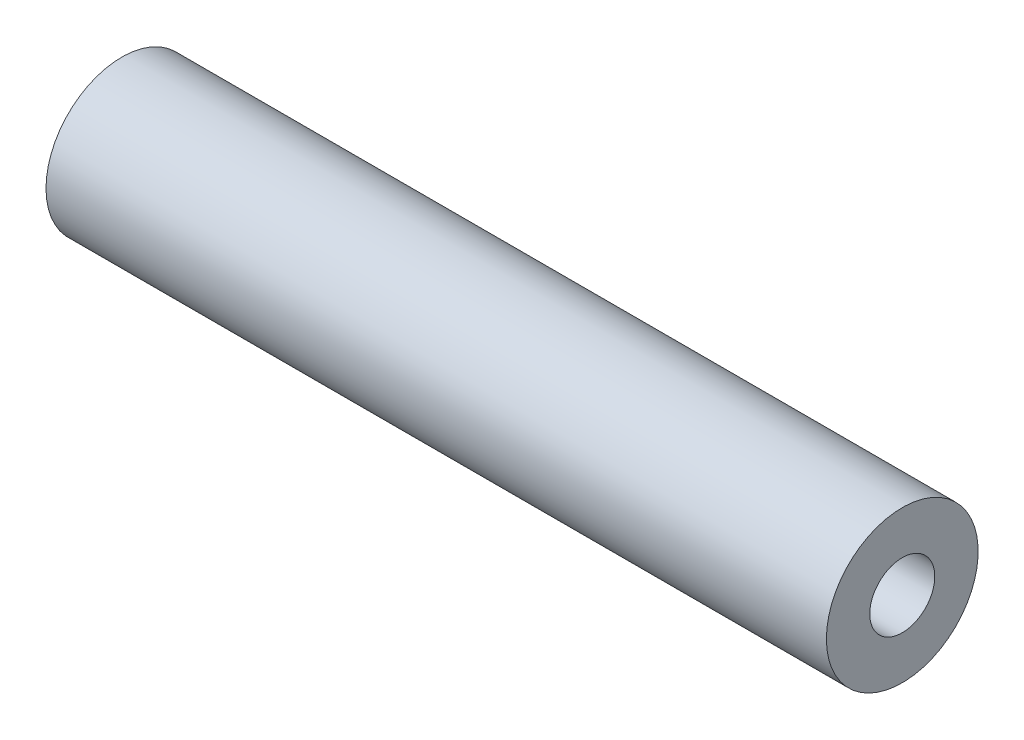
SolidWorks part; units mm, degrees
ref_plane "Front Plane" through (0, 0, 0) normal (0, 0, 1) x (1, 0, 0)
ref_plane "Top Plane" through (0, 0, 0) normal (0, 1, 0) x (1, 0, 0)
ref_plane "Right Plane" through (0, 0, 0) normal (1, 0, 0) x (0, 0, -1)
sketch "Sketch1" plane through (0, 0, 0) normal (0, 0, 1) x (1, 0, 0)
  line L0 (0, 0) -> (240, 0) construction
  line L1 (30, 7.5) -> (210, 7.5)
  line L6 (30, 17.5) -> (210, 17.5)
  line L7 (30, 17.5) -> (30, 7.5)
  line L9 (210, 17.5) -> (210, 7.5)
  dimension "L" = 240
  dimension "D_s" = 15
  dimension "D" = 35
revolve "Revolve1" add sketch "Sketch1" angle 360 about L0
